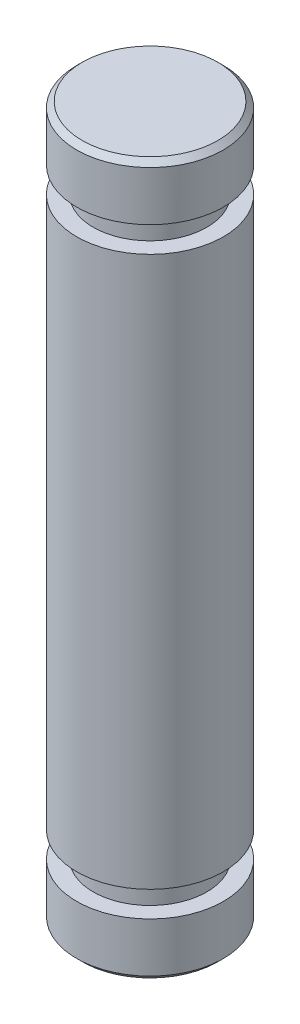
SolidWorks part; units mm, degrees
ref_plane "Front Plane" through (0, 0, 0) normal (0, 0, 1) x (1, 0, 0)
ref_plane "Top Plane" through (0, 0, 0) normal (0, 1, 0) x (1, 0, 0)
ref_plane "Right Plane" through (0, 0, 0) normal (1, 0, 0) x (0, 0, -1)
sketch "Sketch1" plane through (0, 0, 0) normal (0, 0, 1) x (1, 0, 0)
  line L0 (0, 0) -> (0, 19.4)
  line L1 (0, 19.4) -> (2, 19.4)
  line L2 (2, 19.4) -> (2, 17.9)
  line L3 (2, 17.9) -> (1.55, 17.9)
  line L4 (1.55, 17.9) -> (1.55, 17.2)
  line L5 (1.55, 17.2) -> (2, 17.2)
  line L6 (2, 17.2) -> (2, 2.2)
  line L7 (2, 2.2) -> (1.55, 2.2)
  line L8 (1.55, 2.2) -> (1.55, 1.5)
  line L9 (1.55, 1.5) -> (2, 1.5)
  line L10 (2, 1.5) -> (2, 0)
  line L11 (2, 0) -> (0, 0)
  dimension "D1" = 0.7
  dimension "D2" = 0.7
  dimension "D3" = 15
  dimension "D4" = 1.5
  dimension "D5" = 1.5
  dimension "D6" = 1.55
  dimension "D7" = 2
revolve "Revolve1" add sketch "Sketch1" angle 360 about L0
chamfer "Chamfer1" distance 0.15 angle 45 2 edges at (0, 19.4, -2) (0, 0, -2)
